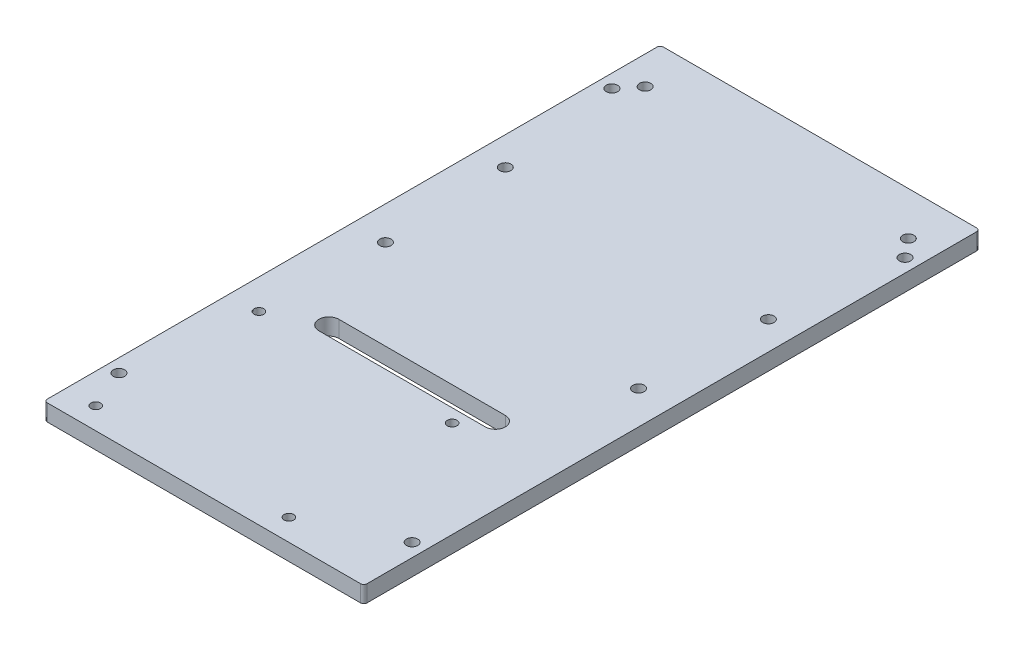
SolidWorks part; units mm, degrees
other "cable-slot"
ref_plane "Front Plane" through (0, 0, 0) normal (0, 0, 1) x (1, 0, 0)
ref_plane "Top Plane" through (0, 0, 0) normal (0, 1, 0) x (1, 0, 0)
ref_plane "Right Plane" through (0, 0, 0) normal (1, 0, 0) x (0, 0, -1)
sketch "Sketch1" plane through (0, 0, 0) normal (0, 1, 0) x (1, 0, 0)
  line L1 (-48, 92.5) -> (48, 92.5)
  line L2 (-48, 92.5) -> (-48, -92.5)
  line L3 (-48, -92.5) -> (48, -92.5)
  line L4 (48, 92.5) -> (48, -92.5)
  line L5 (-48, 92.5) -> (48, -92.5) construction
  line L6 (-48, -92.5) -> (48, 92.5) construction
  point P0 (0, 0)
  dimension "D1" = 96
  dimension "D2" = 185
extrude "plate" add sketch "Sketch1" along normal blind 5
sketch "Sketch2" plane through (0, 5, 0) normal (0, 1, 0) x (1, 0, 0)
  line L0 (-44, 74) -> (44, 74) construction
  line L1 (-44, 74) -> (-44, -74) construction
  circle A0 centre (44, 74) radius 1.7
  circle A1 centre (-44, 74) radius 1.7
  circle A2 centre (44, -74) radius 1.7
  circle A3 centre (-44, -74) radius 1.7
  point P8 (-44, 0)
  point P9 (0, 74)
  dimension "D1" = 3.4
  dimension "D2" = 44
  dimension "D3" = 74
extrude "standoff-holes" cut sketch "Sketch2" against normal up to next
sketch "Sketch3" plane through (0, 5, 0) normal (0, 1, 0) x (1, 0, 0)
  line L0 (-38, 0) -> (38, 0) construction
  circle A0 centre (38, 0) radius 1.7
  circle A1 centre (-38, 0) radius 1.7
  point P4 (0, 0)
  dimension "D1" = 3.4
  dimension "D2" = 76
extrude "power-board-holes" cut sketch "Sketch3" against normal up to next
fillet "Fillet1" radius 1 4 edges at (-48, 2.5, -92.5) (48, 2.5, -92.5) (48, 2.5, 92.5) (-48, 2.5, 92.5)
hole_wizard "M2.5 Clearance Hole1" positions "Sketch8" profile "Sketch9" hole size "M2.5" standard "AS" end condition up to next
sketch "Sketch8" plane through (0, 5, 0) normal (0, 1, 0) x (1, 0, 0)
  point P0 (-39, -85.98)
  point P3 (19, -85.98)
  point P6 (-39, -36.98)
  point P9 (19, -36.98)
sketch "Sketch9" plane through (-39, 5, 85.98) normal (1, 0, 0) x (0, 0, 1)
  line L0 (0, 0) -> (0, 5)
  line L1 (0, 5) -> (1.45, 5)
  line L2 (1.45, 5) -> (1.45, 0)
  line L5 (1.45, 0) -> (0, 0)
  line L11 (0, -6.35) -> (0, 107.95) construction
  dimension "Thru Hole Dia." = 2.9
  dimension "Thru Hole Depth" = 5
hole_wizard "M3 Clearance Hole2" positions "Sketch10" profile "Sketch11" hole size "M3" standard "AS" end condition up to next
sketch "Sketch10" plane through (0, 5, 0) normal (0, 1, 0) x (1, 0, 0)
  point P0 (-39.5, 79.48)
  point P3 (-39.5, 37.48)
  point P6 (39.5, 37.48)
  point P9 (39.5, 79.48)
sketch "Sketch11" plane through (-39.5, 5, -79.48) normal (1, 0, 0) x (0, 0, 1)
  line L0 (0, 0) -> (0, 5)
  line L1 (0, 5) -> (1.7, 5)
  line L2 (1.7, 5) -> (1.7, 0)
  line L5 (1.7, 0) -> (0, 0)
  line L11 (0, -6.35) -> (0, 107.95) construction
  dimension "Thru Hole Dia." = 3.4
  dimension "Thru Hole Depth" = 5
sketch "Sketch12" plane through (0, 5, 0) normal (0, 1, 0) x (1, 0, 0)
  line L0 (-25, -30) -> (25, -30) construction
  line L1 (-25, -27) -> (25, -27)
  line L2 (-25, -33) -> (25, -33)
  arc A0 (-25, -27) -> (-25, -33) centre (-25, -30) ccw
  arc A1 (25, -33) -> (25, -27) centre (25, -30) ccw
  point P2 (0, -30)
  point P7 (0, 0)
  dimension "D2" = 3
  dimension "D3" = 50
  dimension "D1" = 30
extrude "Cut-Extrude1" cut sketch "Sketch12" against normal up to next
